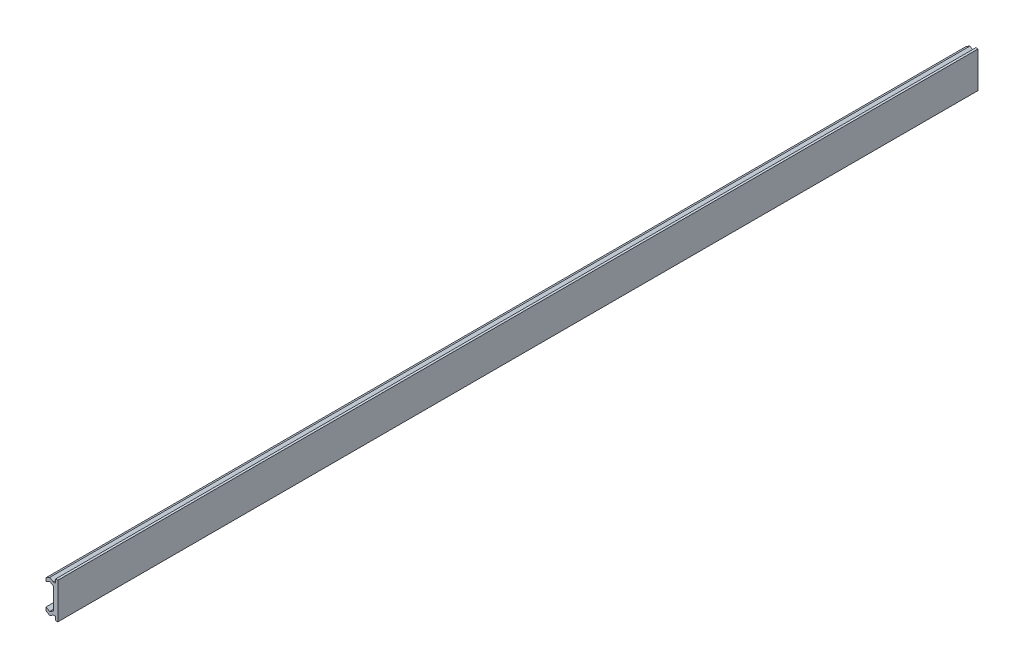
SolidWorks part; units mm, degrees
ref_plane "XY" through (0, 0, 0) normal (0, 0, 1) x (1, 0, 0)
ref_plane "XZ" through (0, 0, 0) normal (0, 1, 0) x (1, 0, 0)
ref_plane "YZ" through (0, 0, 0) normal (1, 0, 0) x (0, 0, -1)
sketch "Sketch1" plane through (0, 0, 0) normal (0, 0, 1) x (1, 0, 0)
  line L0 (0, -4.9) -> (0, 4.9)
  line L1 (0, 4.9) -> (-0.6, 4.9)
  line L2 (-0.6, 4.9) -> (-0.6, 3.9)
  line L3 (-0.6, 3.9) -> (-1.2, 3.9)
  line L4 (-1.2, 3.9) -> (-2.2, 4.4774)
  line L5 (-2.2, 4.4774) -> (-3.2, 3.9)
  line L6 (-3.2, 3.9) -> (-3.2, 2.975)
  line L7 (-3.2, 2.975) -> (-2.2, 3.5524)
  line L8 (-2.2, 3.5524) -> (-1.2, 2.975)
  line L9 (-1.2, 2.975) -> (-1.2, -2.975)
  line L10 (-1.2, 0) -> (0, 0) construction
  line L11 (-2.2, -3.5524) -> (-1.2, -2.975)
  line L12 (-3.2, -2.975) -> (-2.2, -3.5524)
  line L13 (-3.2, -3.9) -> (-3.2, -2.975)
  line L14 (-2.2, -4.4774) -> (-3.2, -3.9)
  line L15 (-1.2, -3.9) -> (-2.2, -4.4774)
  line L16 (-0.6, -3.9) -> (-1.2, -3.9)
  line L17 (-0.6, -4.9) -> (-0.6, -3.9)
  line L18 (0, -4.9) -> (-0.6, -4.9)
  dimension "D1" = 4.9
  dimension "D2" = 0.6
  dimension "D3" = 0.6
  dimension "D4" = 1.2
  dimension "D5" = 1
  dimension "D6" = 1
  dimension "D7" = 0.925
  dimension "D8" = 2.975
  dimension "D9" = 2.6
  dimension "D10" = 120
  dimension "D11" = 150
extrude "Boss-Extrude1" add sketch "Sketch1" along normal mid plane 250
